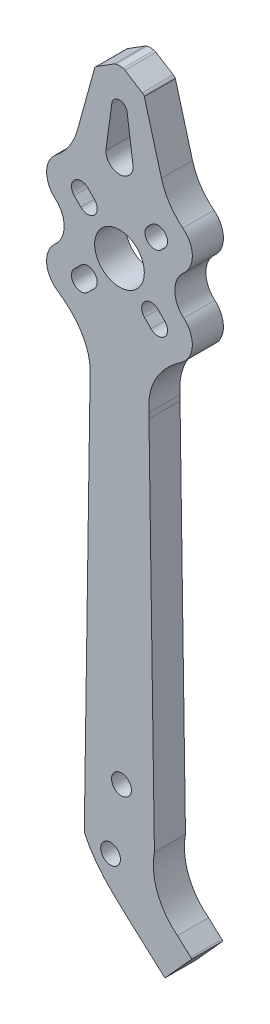
SolidWorks part; units mm, degrees
ref_plane "Alzado" through (0, 0, 0) normal (0, 0, 1) x (1, 0, 0)
ref_plane "Planta" through (0, 0, 0) normal (0, 1, 0) x (1, 0, 0)
ref_plane "Vista lateral" through (0, 0, 0) normal (1, 0, 0) x (0, 0, -1)
sketch "Croquis1" plane through (0, 0, 0) normal (0, 0, 1) x (1, 0, 0)
  line L0 (-2.1978, 13.916) -> (-1.25, 20.8515)
  line L5 (1.4432, 0) -> (-1.4432, 0) construction
  line L6 (0, 26.8758) -> (0, 27) construction
  line L23 (0, 4) -> (2.2899, 4) construction
  line L25 (2.7136, 13.8515) -> (2.1978, 13.916)
  line L26 (0, 0) -> (0, -80) construction
  line L29 (-5.6262, -80) -> (5.6262, -80) construction
  line L31 (-5.6262, -80) -> (-5.6262, -82.9587)
  line L36 (7.1515, -96.5492) -> (7.3186, -96.6998)
  line L37 (6.204, -95.6953) -> (1.3171, -91.2911)
  line L38 (11.4888, -91.7365) -> (9.346, -89.7768)
  line L39 (-6.1872, 6.1872) -> (-5.1265, 5.1265) construction
  line L40 (-5.0912, 7.2832) -> (-4.0305, 6.2225)
  line L41 (-7.2832, 5.0912) -> (-6.2225, 4.0305)
  line L42 (6.1872, 6.1872) -> (5.1265, 5.1265) construction
  line L47 (-1, 1) -> (1, -1) construction
  line L48 (-1, -1) -> (1, 1) construction
  line L49 (5.0912, 7.2832) -> (4.0305, 6.2225)
  line L50 (7.2832, 5.0912) -> (6.2225, 4.0305)
  line L51 (-6.1872, -6.1872) -> (-5.1265, -5.1265) construction
  line L52 (-5.0912, -7.2832) -> (-4.0305, -6.2225)
  line L53 (-7.2832, -5.0912) -> (-6.2225, -4.0305)
  line L54 (6.1872, -6.1872) -> (5.1265, -5.1265) construction
  line L55 (5.0912, -7.2832) -> (4.0305, -6.2225)
  line L56 (7.2832, -5.0912) -> (6.2225, -4.0305)
  line L57 (6.204, -95.6953) -> (7.1515, -96.5492)
  line L58 (2.1978, 13.916) -> (1.25, 20.8515)
  line L59 (0, 26.8758) -> (0, 22.1015)
  line L60 (-3.6556, 24.9413) -> (-0.8682, 26.6832)
  line L61 (3.6556, 24.9413) -> (0.8682, 26.6832)
  line L62 (-6.7596, 14.5341) -> (-4, 24.5786)
  line L63 (-10.2131, 9.3289) -> (-10.2129, 9.329)
  line L64 (-4.75, -19.1024) -> (-4.75, -20)
  line L65 (-5.6262, -80) -> (-4.75, -20)
  line L66 (5.6262, -80) -> (4.75, -20)
  line L67 (4.75, -19.1024) -> (4.75, -20)
  line L68 (6.7596, 14.5341) -> (4, 24.5786)
  line L69 (-8.5, 0) -> (-4, 0) construction
  line L71 (7.3186, -96.6998) -> (11.6559, -91.8871)
  line L72 (11.4888, -91.7365) -> (11.6559, -91.8871)
  arc A0 (-6.7529, 4.5608) -> (-6.6415, 4.4598) centre (-5.6569, 5.6569) ccw
  circle A1 centre (-5.6569, -5.6569) radius 1.55
  circle A2 centre (5.6569, -5.6569) radius 1.55
  circle A3 centre (5.6569, 5.6569) radius 1.55
  circle A5 centre (0, 0) radius 4
  arc A11 (-6.6415, -4.4598) -> (-4.4598, -6.6415) centre (0, 0) ccw
  arc A14 (4.4598, -6.6415) -> (6.6415, -4.4598) centre (0, 0) ccw
  arc A15 (6.6415, 4.4598) -> (4.4598, 6.6415) centre (0, 0) ccw
  arc A22 (0.5754, 26.8066) -> (-0.5754, 26.8066) centre (0, 24.4495) ccw
  arc A33 (9.346, -89.7768) -> (5.6262, -80) centre (15.4522, -81.8575) cw
  arc A36 (-5.0912, 7.2832) -> (-7.2832, 5.0912) centre (-6.1872, 6.1872) ccw
  arc A37 (-6.2225, 4.0305) -> (-4.0305, 6.2225) centre (-5.1265, 5.1265) ccw
  arc A38 (-4.4598, 6.6415) -> (-4.5608, 6.7529) centre (-5.6569, 5.6569) ccw
  arc A39 (5.0912, 7.2832) -> (7.2832, 5.0912) centre (6.1872, 6.1872) cw
  arc A40 (6.2225, 4.0305) -> (4.0305, 6.2225) centre (5.1265, 5.1265) cw
  arc A41 (-5.0912, -7.2832) -> (-7.2832, -5.0912) centre (-6.1872, -6.1872) cw
  arc A42 (-6.2225, -4.0305) -> (-4.0305, -6.2225) centre (-5.1265, -5.1265) cw
  arc A43 (5.0912, -7.2832) -> (7.2832, -5.0912) centre (6.1872, -6.1872) ccw
  arc A44 (6.2225, -4.0305) -> (4.0305, -6.2225) centre (5.1265, -5.1265) ccw
  arc A45 (1.25, 20.8515) -> (-1.25, 20.8515) centre (0, 20.8515) ccw
  arc A46 (-2.1978, 13.916) -> (2.1978, 13.916) centre (0, 13.916) ccw
  arc A47 (-0.5754, 26.8066) -> (-0.8682, 26.6832) centre (-0.3383, 25.8351) ccw
  arc A48 (-3.6556, 24.9413) -> (-4, 24.5786) centre (-3.1256, 24.0933) ccw
  arc A51 (0.5754, 26.8066) -> (0.8682, 26.6832) centre (0.3383, 25.8351) cw
  arc A52 (3.6556, 24.9413) -> (4, 24.5786) centre (3.1256, 24.0933) cw
  arc A53 (-6.7596, 14.5341) -> (-10.2129, 9.329) centre (-16.4023, 17.1834) cw
  arc A64 (0.1516, 3.9971) -> (0.1507, 4) centre (5.6569, 5.6569) cw
  arc A65 (-10.3568, -3.1643) -> (-10.3568, 3.1643) centre (-13.099, 0) ccw
  arc A66 (6.5746, 4.3826) -> (6.5612, 4.3981) centre (8.6497, 6.1872) cw
  arc A67 (6.5746, -4.3826) -> (6.5612, -4.3981) centre (8.6497, -6.1872) ccw
  arc A68 (-6.5746, -4.3826) -> (-6.5612, -4.3981) centre (-8.6497, -6.1872) cw
  arc A70 (-10.2129, 9.329) -> (-10.3568, 3.1643) centre (-7.7372, 6.1872) ccw
  arc A71 (10.2129, 9.329) -> (10.3568, 3.1643) centre (7.7372, 6.1872) cw
  arc A72 (10.3568, -3.1643) -> (10.3568, 3.1643) centre (13.099, 0) cw
  arc A73 (9.9986, -9.4866) -> (10.3568, -3.1643) centre (7.7372, -6.1872) ccw
  arc A74 (-4.6412, -3.6545) -> (-3.752, -5.8429) centre (-7.7372, -6.1872) cw
  arc A75 (6.7596, 14.5341) -> (10.2129, 9.329) centre (16.4023, 17.1834) ccw
  arc A76 (-9.9986, -9.4866) -> (-10.3568, -3.1643) centre (-7.7372, -6.1872) cw
  circle A77 centre (0.324, -73.2048) radius 1.5974
  circle A78 centre (-1.4339, -83.7443) radius 1.59
  spline S0 degree 3 poles (-4.75, -19.1024) (-4.3548, -14.7385) (-6.9802, -11.5418) (-9.9986, -9.4866) knots 0 0 0 0 1 1 1 1
  spline S1 degree 3 poles (-5.6262, -82.9587) (-3.958, -86.469) (-1.3336, -88.8938) (1.4881, -91.4459) (1.5742, -91.5229) knots 0 0 0 0 0.775056 0.79931 0.79931 0.79931 0.79931
  spline S2 degree 3 poles (4.75, -19.1024) (4.3548, -14.7385) (6.9802, -11.5418) (9.9986, -9.4866) knots 0 0 0 0 1 1 1 1
  point P58 (3.0973, 26.3745)
  point P64 (-3.0973, 26.3745)
  point P77 (4.2446, 10.2207)
  point P81 (-4.2446, 10.2207)
  point P95 (-5.6569, 5.6569)
  point P109 (5.6569, 5.6569)
  point P116 (-5.6569, -5.6569)
  point P123 (5.6569, -5.6569)
  dimension "D1" = 3.1
  dimension "D4" = 23
  dimension "D3" = 8
  dimension "D7" = 4.75
  dimension "D8" = 8
  dimension "D9" = 7
  dimension "D13" = 0.225
  dimension "D14" = 10
  dimension "D12" = 80
  dimension "D17" = 2.9587
  dimension "D18" = 2.8864
  dimension "D19" = 45
  dimension "D22" = 2.5
  dimension "D23" = 1
  dimension "D6" = 4.5
  dimension "D20" = 10
  dimension "D2" = 16
  dimension "D5" = 11.3137
  dimension "D10" = 7
  dimension "D11" = 5.6262
  dimension "D15" = 2
  dimension "D16" = 2
  dimension "D21" = 1.5
extrude "Saliente-Extruir1" add sketch "Croquis1" along normal blind 5
